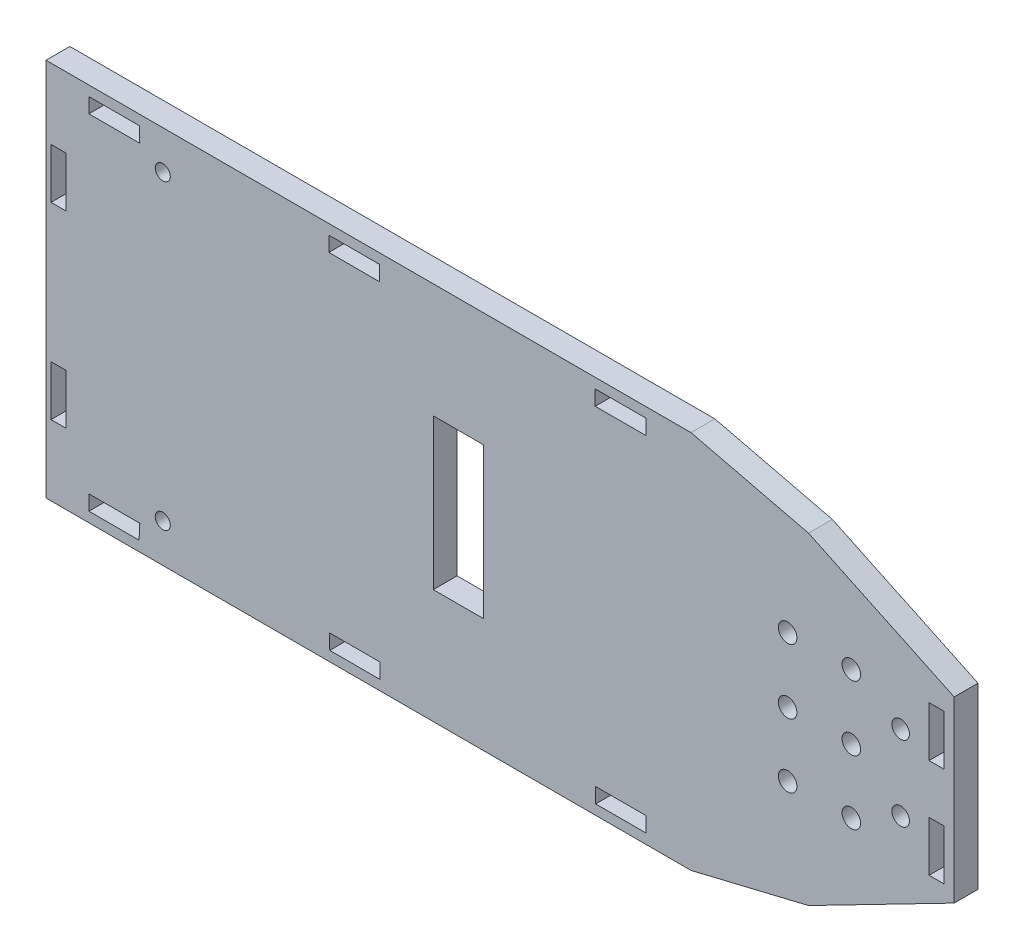
SolidWorks part; units mm, degrees
ref_plane "Front Plane" through (0, 0, 0) normal (0, 0, 1) x (1, 0, 0)
ref_plane "Top Plane" through (0, 0, 0) normal (0, 1, 0) x (1, 0, 0)
ref_plane "Right Plane" through (0, 0, 0) normal (1, 0, 0) x (0, 0, -1)
sketch "Sketch1" plane through (0, 0, 0) normal (0, 0, 1) x (1, 0, 0)
  line L1 (-90.5, -37.785) -> (90.5, -37.785)
  line L2 (-90.5, -37.785) -> (-90.5, 37.785)
  line L3 (-90.5, 37.785) -> (90.5, 37.785)
  line L4 (90.5, -37.785) -> (90.5, 37.785)
  line L5 (-90.5, -37.785) -> (90.5, 37.785) construction
  line L6 (-90.5, 37.785) -> (90.5, -37.785) construction
  point P0 (0, 0)
extrude "Boss-Extrude2" add sketch "Sketch1" along normal blind 4.75
sketch "Sketch6" plane through (0, 0, 4.75) normal (0, 0, 1) x (1, 0, 0)
  line L0 (-90.5, 0) -> (90.5, 0) construction
  line L1 (-90.5, 37.785) -> (-90.5, -37.785) construction
  line L2 (90.5, -37.785) -> (90.5, 37.785) construction
  line L3 (0, 37.785) -> (0, -37.785) construction
  line L4 (90.5, 37.785) -> (-90.5, 37.785) construction
  line L5 (-90.5, -37.785) -> (90.5, -37.785) construction
  line L10 (-17.18, 37.785) -> (-17.18, -37.785) construction
  line L11 (-81.9552, 32.802) -> (-71.8128, 32.7986)
  line L12 (-89.5, 23.75) -> (-86.5, 23.75)
  line L13 (-89.5, 23.75) -> (-89.5, 13.75)
  line L14 (-89.5, 13.75) -> (-86.5, 13.75)
  line L15 (-86.5, 23.75) -> (-86.5, 13.75)
  line L16 (-89.5, -13.75) -> (-86.5, -13.75)
  line L17 (-89.5, -13.75) -> (-89.5, -23.75)
  line L18 (-89.5, -23.75) -> (-86.5, -23.75)
  line L19 (-86.5, -13.75) -> (-86.5, -23.75)
  line L20 (-34.1308, 32.7983) -> (-34.1388, 35.785)
  line L21 (-34.1308, 32.7983) -> (-24.043, 32.7816)
  line L22 (-34.1388, 35.785) -> (-24.043, 35.785)
  line L23 (-24.043, 32.7816) -> (-24.043, 35.785)
  line L24 (-71.8128, 32.7986) -> (-71.8594, 35.785)
  line L25 (-81.9552, 32.802) -> (-81.9552, 35.785)
  line L26 (-81.9552, 35.785) -> (-71.8594, 35.785)
  line L27 (-81.9552, -32.785) -> (-71.8128, -32.7884)
  line L28 (-71.9552, -35.785) -> (-71.8128, -32.7884)
  line L29 (-81.9552, -35.785) -> (-71.9552, -35.785)
  line L30 (-81.9552, -35.785) -> (-81.9552, -32.785)
  line L31 (-33.9472, -35.801) -> (-23.9472, -35.8088)
  line L32 (-33.9472, -35.801) -> (-33.9552, -32.801)
  line L33 (-23.9472, -35.8088) -> (-23.9469, -32.8043)
  line L34 (-33.9552, -32.801) -> (-23.9469, -32.8043)
  line L35 (85.5, 14.9) -> (85.5, 4.9)
  line L36 (88.5, 14.9) -> (88.5, 4.9)
  line L37 (85.5, 4.9) -> (88.5, 4.9)
  line L38 (85.5, 14.9) -> (88.5, 14.9)
  line L39 (88.5, 9.9) -> (85.5, 9.9) construction
  line L40 (29.0528, 32.7816) -> (29.0528, 35.785)
  line L41 (18.957, 32.7816) -> (29.0528, 32.7816)
  line L42 (18.957, 32.7816) -> (18.957, 35.785)
  line L43 (18.957, 35.785) -> (29.0528, 35.785)
  line L44 (19.0531, -32.8054) -> (29.0528, -32.8063)
  line L45 (19.0528, -35.8054) -> (19.0531, -32.8054)
  line L46 (19.0528, -35.8054) -> (29.0528, -35.8063)
  line L47 (29.0528, -35.8063) -> (29.0528, -32.8063)
  line L50 (-67.23, -30.095) -> (79.8334, -30.095) construction
  line L51 (-13.3116, 15) -> (-3.3116, 15)
  line L52 (-13.3116, 15) -> (-13.3116, -15)
  line L53 (-13.3116, -15) -> (-3.3116, -15)
  line L54 (-3.3116, 15) -> (-3.3116, -15)
  line L59 (85.5, -14.9) -> (88.5, -14.9)
  line L64 (85.5, -4.9) -> (85.5, -14.9)
  line L65 (85.5, -4.9) -> (88.5, -4.9)
  line L66 (88.5, -4.9) -> (88.5, -14.9)
  line L67 (38.0552, -37.785) -> (61.4663, -32.14)
  line L68 (61.4663, -32.14) -> (90.5, -17.2)
  line L69 (38.0552, 37.785) -> (61.4663, 32.14)
  line L70 (61.4663, 32.14) -> (90.5, 18.3856)
  line L71 (79.8334, -30.095) -> (79.8334, -36.495)
  circle A2 centre (-67.23, 30.095) radius 1.5
  circle A3 centre (-67.23, -30.095) radius 1.5
  circle A12 centre (70.0065, -12.7534) radius 1.85
  circle A13 centre (70.0065, 12.8925) radius 1.85
  circle A14 centre (70.0065, 0) radius 1.85
  circle A15 centre (57.3065, 12.8925) radius 1.85
  circle A16 centre (57.3065, 0) radius 1.85
  circle A17 centre (57.3065, -12.7534) radius 1.85
  circle A20 centre (79.8334, -7.5) radius 1.75
  circle A21 centre (79.8334, 7.5) radius 1.75
  point P21 (90.5, 0)
  dimension "D1" = 43
  dimension "D3" = 27.5
  dimension "D2" = 43
  dimension "D4" = 15
  dimension "D6" = 2
  dimension "D5" = 7.5
  dimension "D7" = 2
  dimension "D8" = 2
  dimension "D9" = 2
  dimension "D10" = 1
  dimension "D11" = 13.75
  dimension "D12" = 10
extrude "Cut-Extrude7" cut sketch "Sketch6" against normal blind 9
